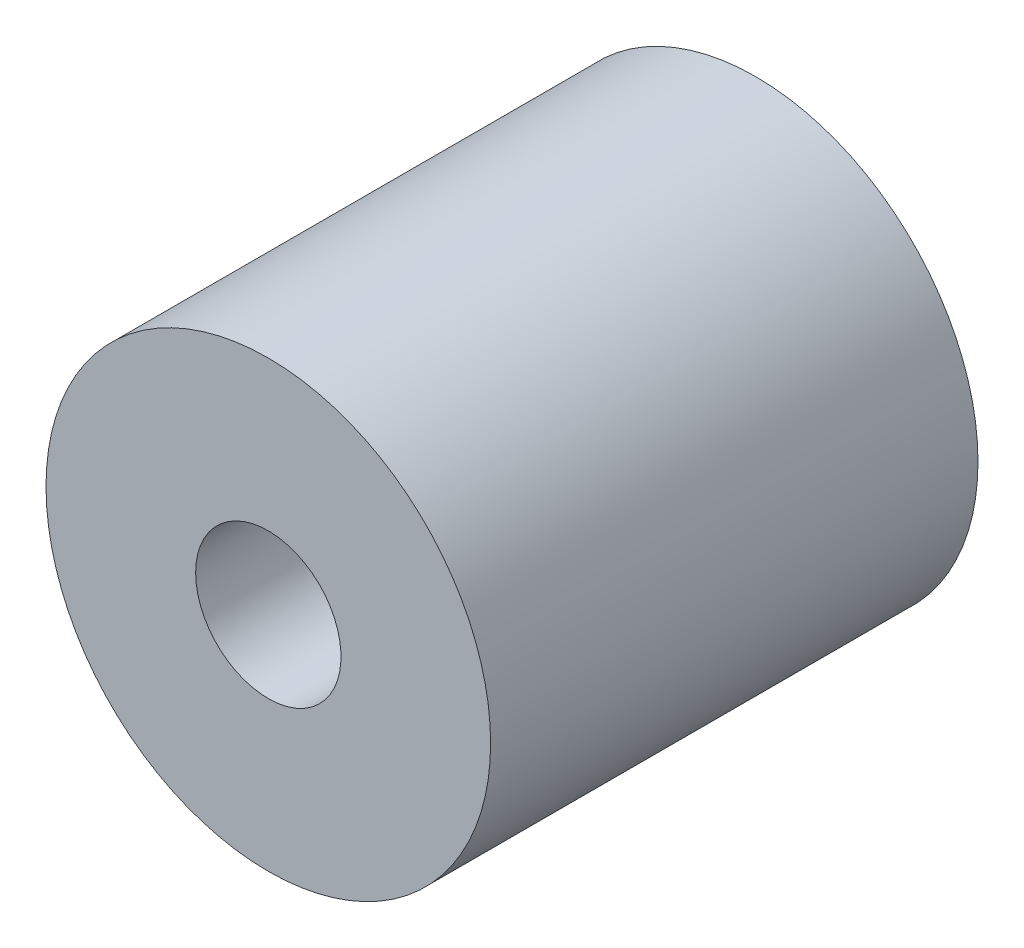
SolidWorks part; units mm, degrees
ref_plane "Front" through (0, 0, 0) normal (0, 0, 1) x (1, 0, 0)
ref_plane "Top" through (0, 0, 0) normal (0, 1, 0) x (1, 0, 0)
ref_plane "Right" through (0, 0, 0) normal (1, 0, 0) x (0, 0, -1)
sketch "Sketch1" plane through (0, 0, 0) normal (0, 0, 1) x (1, 0, 0)
  circle A0 centre (0, 0) radius 26
  circle A1 centre (0, 0) radius 8.5
  dimension "D1" = 52
  dimension "D2" = 17
extrude "Boss-Extrude1" add sketch "Sketch1" along normal blind 57
